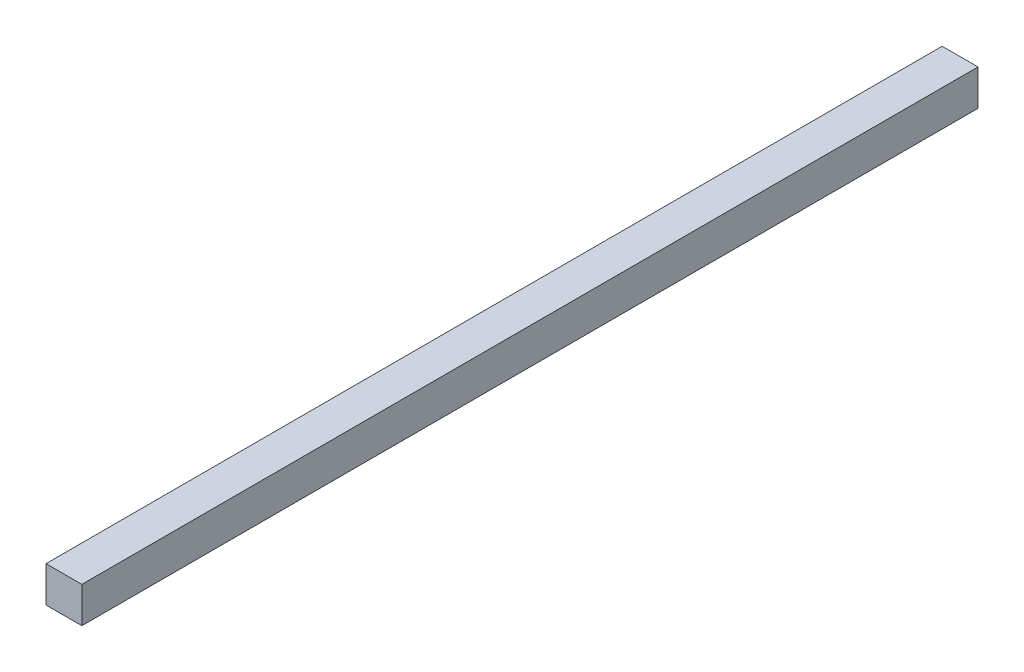
SolidWorks part; units mm, degrees
ref_plane "前基準面" through (0, 0, 0) normal (0, 0, 1) x (1, 0, 0)
ref_plane "上基準面" through (0, 0, 0) normal (0, 1, 0) x (1, 0, 0)
ref_plane "右基準面" through (0, 0, 0) normal (1, 0, 0) x (0, 0, -1)
sketch "草圖1" plane through (0, 0, 0) normal (0, 0, 1) x (1, 0, 0)
  line L1 (-10, 10) -> (10, 10)
  line L2 (-10, 10) -> (-10, -10)
  line L3 (-10, -10) -> (10, -10)
  line L4 (10, 10) -> (10, -10)
  point P4 (0, 10)
  point P6 (-10, 0)
  dimension "D1" = 20
  dimension "D2" = 20
extrude "填料-伸長1" add sketch "草圖1" along normal blind 500
sketch "草圖2" plane through (0, 10, 0) normal (0, 1, 0) x (1, 0, 0)
  line L0 (0, 0) -> (0, -500) construction
  line L1 (10, 0) -> (-10, 0) construction
  line L2 (10, -500) -> (-10, -500) construction
sketch "草圖3" plane through (10, 0, 0) normal (1, 0, 0) x (0, 0, -1)
  line L0 (0, 0) -> (-500, 0) construction
  line L1 (0, -10) -> (0, 10) construction
  line L2 (-500, -10) -> (-500, 10) construction
sketch "草圖4" plane through (0, -10, 0) normal (0, -1, 0) x (1, 0, 0)
  line L0 (0, 0) -> (0, 500) construction
sketch "草圖5" plane through (-10, 0, 0) normal (-1, 0, 0) x (0, 0, 1)
  line L0 (0, 0) -> (500, 0) construction
sketch "草圖7" plane through (0, 10, 0) normal (0, 1, 0) x (1, 0, 0)
  line L0 (-10, -420) -> (10, -420) construction
  line L1 (-10, -500) -> (-10, 0) construction
  line L2 (10, -500) -> (10, 0) construction
  line L3 (10, -500) -> (-10, -500) construction
  dimension "D1" = 80
sketch "草圖8" plane through (10, 0, 0) normal (1, 0, 0) x (0, 0, -1)
  line L0 (-570.1497, 10) -> (-570.1497, -10) construction
  line L1 (-500, 10) -> (0, 10) construction
  line L2 (-500, -10) -> (0, -10) construction
sketch "草圖9" plane through (0, -10, 0) normal (0, -1, 0) x (1, 0, 0)
  line L0 (10, 420) -> (-10, 420) construction
  line L1 (-10, 500) -> (-10, 0) construction
sketch "草圖10" plane through (-10, 0, 0) normal (-1, 0, 0) x (0, 0, 1)
  line L0 (570.1497, -10) -> (570.1497, 10) construction
